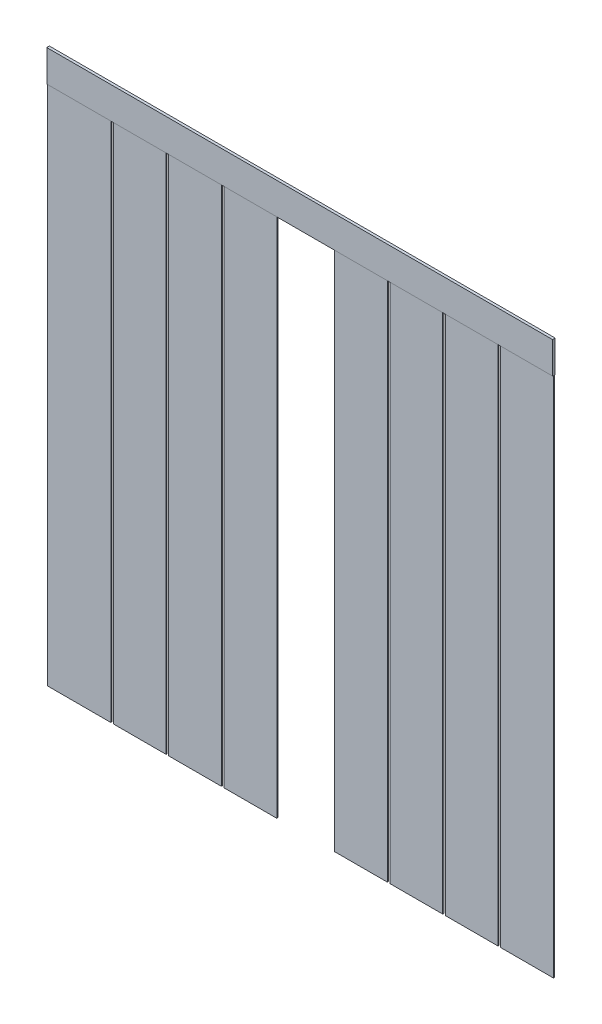
SolidWorks part; units mm, degrees
ref_plane "Alzado" through (0, 0, 0) normal (0, 0, 1) x (1, 0, 0)
ref_plane "Planta" through (0, 0, 0) normal (0, 1, 0) x (1, 0, 0)
ref_plane "Vista lateral" through (0, 0, 0) normal (1, 0, 0) x (0, 0, -1)
sketch "Croquis1" plane through (0, 0, 0) normal (0, 0, 1) x (1, 0, 0)
  line L1 (0, 0) -> (1920, 0)
  line L2 (0, 0) -> (0, -2100)
  line L3 (0, -2100) -> (1920, -2100)
  line L4 (1920, 0) -> (1920, -2100)
  dimension "D1" = 1920
  dimension "D2" = 2100
extrude "Saliente-Extruir1" add sketch "Croquis1" along normal blind 10
sketch "Croquis2" plane through (0, 0, 10) normal (0, 0, 1) x (1, 0, 0)
  line L0 (1920, -2100) -> (1920, 0) construction
  line L1 (0, -2100) -> (1920, -2100)
  line L2 (0, -2100) -> (0, -120)
  line L3 (0, -120) -> (1920, -120)
  line L4 (1920, -2100) -> (1920, -120)
  line L5 (1920, 0) -> (0, 0) construction
  dimension "D1" = 120
extrude "Cortar-Extruir1" cut sketch "Croquis2" against normal blind 3
sketch "Croquis3" plane through (0, 0, 0) normal (0, 0, -1) x (-1, 0, 0)
  line L1 (-1920, -2100) -> (0, -2100)
  line L2 (-1920, -2100) -> (-1920, -120)
  line L3 (-1920, -120) -> (0, -120)
  line L4 (0, -2100) -> (0, -120)
extrude "Cortar-Extruir2" cut sketch "Croquis3" against normal blind 3
sketch "Croquis4" plane through (0, 0, 3) normal (0, 0, -1) x (-1, 0, 0)
  line L0 (-1920, -2100) -> (0, -2100) construction
  line L1 (-1720, -2100) -> (-1710, -2100)
  line L2 (-1720, -2100) -> (-1720, -120)
  line L3 (-1720, -120) -> (-1710, -120)
  line L4 (-1710, -2100) -> (-1710, -120)
  line L5 (0, -120) -> (-1920, -120) construction
  line L6 (-1920, -120) -> (-1920, -2100) construction
  dimension "D1" = 200
  dimension "D2" = 10
extrude "Cortar-Extruir3" cut sketch "Croquis4" against normal blind 8
pattern_linear "MatrizL1" count 8 spacing 210 along (-1, 0, 0) of "Cortar-Extruir3"
sketch "Croquis5" plane through (0, 0, 3) normal (0, 0, -1) x (-1, 0, 0)
  line L1 (-1080, -120) -> (-880, -120)
  line L2 (-1080, -120) -> (-1080, -2100)
  line L3 (-1080, -2100) -> (-880, -2100)
  line L4 (-880, -120) -> (-880, -2100)
extrude "Cortar-Extruir4" cut sketch "Croquis5" against normal blind 10
